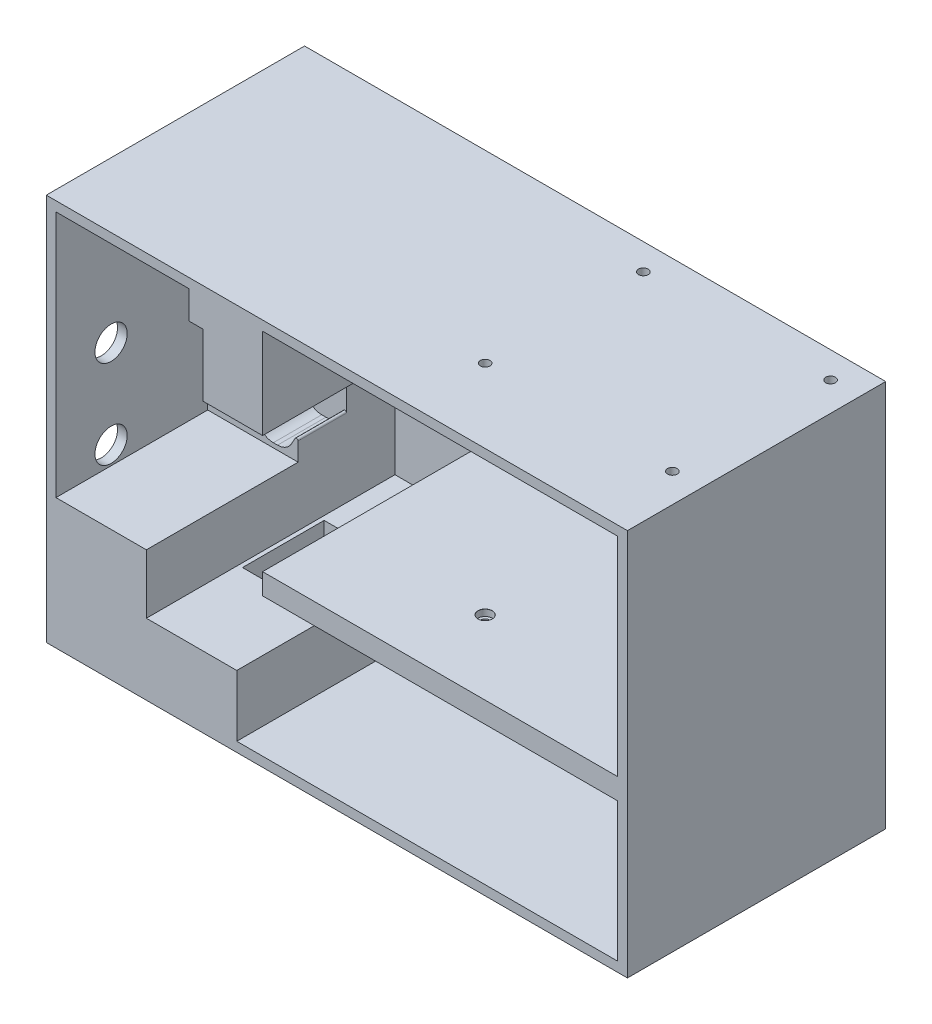
SolidWorks part; units mm, degrees
other "Electronics Cartridge"
ref_plane "Front Plane" through (0, 0, 0) normal (1, 0, 0) x (0, 1, 0)
ref_plane "Top Plane" through (0, 0, 0) normal (0, 0, 1) x (0, 1, 0)
ref_plane "Right Plane" through (0, 0, 0) normal (0, 1, 0) x (-1, 0, 0)
sketch "Sketch1" plane through (0, 0, 0) normal (0, 0, 1) x (0, 1, 0)
  line L1 (60, -90) -> (-60, -90)
  line L2 (60, -90) -> (60, 90)
  line L3 (60, 90) -> (-60, 90)
  line L4 (-60, -90) -> (-60, 90)
  line L5 (60, -90) -> (-60, 90) construction
  line L6 (60, 90) -> (-60, -90) construction
  point P0 (0, 0)
  dimension "D1" = 120
  dimension "D2" = 180
extrude "Boss-Extrude1" add sketch "Sketch1" along normal blind 80
extrude "Cut-Extrude2" cut sketch "Sketch4" against normal blind 77
sketch "Sketch4" plane through (-1315.6499, -737.3472, 80) normal (0, 0, 1) x (1, 0, 0)
  line L4 (1289.6499, 766.3472) -> (1256.6499, 766.3472)
  line L6 (1405.6499, 797.3472) -> (1405.6499, 794.3472)
  line L8 (1405.6499, 794.3472) -> (1402.6499, 794.3472)
  line L9 (1405.6499, 677.3472) -> (1405.6499, 680.3472)
  line L10 (1402.6499, 794.3472) -> (1292.6499, 794.3472)
  line L11 (1402.6499, 794.3472) -> (1402.6499, 729.8472)
  line L12 (1402.6499, 729.8472) -> (1292.6499, 729.8472)
  line L13 (1292.6499, 794.3472) -> (1292.6499, 729.8472)
  line L14 (1405.6499, 680.3472) -> (1402.6499, 680.3472)
  line L15 (1225.6499, 797.3472) -> (1225.6499, 794.3472)
  line L16 (1402.6499, 680.3472) -> (1292.6499, 680.3472)
  line L17 (1402.6499, 680.3472) -> (1402.6499, 723.3472)
  line L18 (1402.6499, 723.3472) -> (1292.6499, 723.3472)
  line L19 (1292.6499, 680.3472) -> (1292.6499, 723.3472)
  line L21 (1225.6499, 794.3472) -> (1228.6499, 794.3472)
  line L22 (1225.6499, 677.3472) -> (1267.6499, 677.3472)
  line L23 (1228.6499, 794.3472) -> (1256.6499, 794.3472)
  line L24 (1228.6499, 794.3472) -> (1228.6499, 730.3472)
  line L25 (1228.6499, 730.3472) -> (1256.6499, 730.3472)
  line L26 (1256.6499, 794.3472) -> (1256.6499, 730.3472)
  line L28 (1267.6499, 677.3472) -> (1267.6499, 680.3472)
  line L29 (1289.6499, 699.3472) -> (1292.6499, 699.3472)
  line L30 (1267.6499, 680.3472) -> (1289.6499, 680.3472)
  line L31 (1267.6499, 680.3472) -> (1267.6499, 699.3472)
  line L32 (1267.6499, 699.3472) -> (1289.6499, 699.3472)
  line L33 (1289.6499, 680.3472) -> (1289.6499, 699.3472)
  line L34 (1292.6499, 723.3472) -> (1292.6499, 729.8472)
  line L35 (1292.6499, 699.3472) -> (1289.6499, 699.3472)
  line L36 (1267.6499, 699.3472) -> (1256.6499, 699.3472)
  line L37 (1256.6499, 699.3472) -> (1256.6499, 729.8472)
  line L38 (1292.6499, 794.3472) -> (1289.6499, 794.3472)
  line L39 (1289.6499, 794.3472) -> (1289.6499, 766.3472)
  line L40 (1289.6499, 766.3472) -> (1292.6499, 766.3472)
  line L41 (1256.6499, 794.3472) -> (1289.6499, 794.3472)
  line L42 (1289.6499, 766.3472) -> (1289.6499, 794.3472)
  line L43 (1256.6499, 699.3472) -> (1292.6499, 699.3472)
  line L44 (1256.6499, 699.3472) -> (1256.6499, 766.3472)
  line L45 (1256.6499, 766.3472) -> (1292.6499, 766.3472)
  line L46 (1292.6499, 699.3472) -> (1292.6499, 766.3472)
  line L47 (1289.6499, 794.3472) -> (1256.6499, 794.3472)
  line L48 (1256.6499, 766.3472) -> (1256.6499, 794.3472)
extrude "Cut-Extrude3" cut sketch "Sketch5" against normal up to surface (77 mm away)
sketch "Sketch5" plane through (-1315.6499, -737.3472, 80) normal (0, 0, 1) x (1, 0, 0)
  line L1 (1256.6499, 794.3472) -> (1274.6499, 794.3472)
  line L2 (1256.6499, 794.3472) -> (1256.6499, 766.3472)
  line L3 (1256.6499, 766.3472) -> (1274.6499, 766.3472)
  line L4 (1274.6499, 794.3472) -> (1274.6499, 766.3472)
sketch "Sketch7" plane through (0, 0, 3) normal (0, 0, 1) x (1, 0, 0)
  line L0 (-59, 48.4969) -> (-66.5056, 48.4969)
  line L1 (-67.9618, 57) -> (-66.5056, 48.4969)
  line L2 (-59, 57) -> (-67.9618, 57)
  line L3 (-59, 57) -> (-59, 48.4969)
  line L4 (-78.0382, -7) -> (-79.4944, 1.5031)
  line L5 (-59, 57) -> (-67.9618, 57)
  line L6 (-59, 57) -> (-59, 48.4969)
  line L7 (-59, 48.4969) -> (-66.5056, 48.4969)
  line L8 (-67.9618, 57) -> (-66.5056, 48.4969)
  line L9 (-74.9296, 57) -> (-71.1195, 57)
  line L13 (-87, 1.5031) -> (-79.4944, 1.5031)
  line L14 (-87, -7) -> (-87, 1.5031)
  line L15 (-87, -7) -> (-78.0382, -7)
  line L16 (-78.0382, -7) -> (-77.996, -7)
  line L17 (-87, 1.5031) -> (-79.4944, 1.5031)
  line L18 (-87, -7) -> (-87, 1.5031)
  line L19 (-87, -7) -> (-78.0382, -7)
  line L20 (-79.4944, 1.5031) -> (-77.996, -7)
  line L21 (-79.4944, 1.5031) -> (-77.996, -7)
  line L22 (-87, 1.5031) -> (-79.4944, 1.5031)
  line L23 (-87, -7) -> (-87, 1.5031)
  line L24 (-77.996, -7) -> (-87, -7)
  line L25 (-79.4944, 1.5031) -> (-77.996, -7)
  line L26 (-74.9296, -7) -> (-77.996, -7)
  line L27 (-87, -7) -> (-59, -7)
  line L28 (-59, 57) -> (-59, -7)
  line L29 (-66.5056, 1.5031) -> (-68.004, -7)
  line L30 (-59, 1.5031) -> (-66.5056, 1.5031)
  line L31 (-59, -7) -> (-59, 1.5031)
  line L32 (-87, 57) -> (-59, 57)
  line L33 (-87, 57) -> (-87, -7)
  line L34 (-79.4944, 1.5031) -> (-77.996, -7)
  line L35 (-87, 1.5031) -> (-79.4944, 1.5031)
  line L36 (-87, 1.5031) -> (-87, -7)
  line L37 (-66.5056, 48.4969) -> (-68.004, 57)
  line L38 (-59, 48.4969) -> (-66.5056, 48.4969)
  line L39 (-59, 48.4969) -> (-59, 57)
  line L40 (-71.0704, 57) -> (-71.1195, 47.7071)
  line L42 (-87, 25) -> (-59, 25)
  line L43 (-73, -7) -> (-73, 47.7071)
  line L44 (-87, 48.4969) -> (-87, 56.702)
  line L45 (-87, 48.4969) -> (-79.4944, 48.4969)
  line L46 (-79.4944, 48.4969) -> (-77.996, 57)
  line L47 (-77.996, 57) -> (-74.9296, 57)
  line L48 (-74.9296, 57) -> (-74.8805, 47.7071)
  line L49 (-74.9296, -7) -> (-71.1153, -7)
  line L52 (-74.9296, -7) -> (-74.9296, 1.5031)
  line L53 (-74.9296, -7) -> (-74.8805, 2.2929)
  line L54 (-74.9296, 57) -> (-77.996, 57)
  line L55 (-79.4944, 48.4969) -> (-77.996, 57)
  line L56 (-77.996, 57) -> (-87, 57)
  line L57 (-87, 57) -> (-87, 48.4969)
  line L58 (-87, 48.4969) -> (-79.4944, 48.4969)
  line L59 (-79.4944, 48.4969) -> (-77.996, 57)
  line L60 (-79.4944, 48.4969) -> (-77.996, 57)
  line L61 (-87, 57) -> (-78.0382, 57)
  line L62 (-87, 57) -> (-87, 48.4969)
  line L63 (-87, 48.4969) -> (-79.4944, 48.4969)
  line L65 (-78.0382, 57) -> (-77.996, 57)
  line L66 (-74.9296, 1.5031) -> (-71.1153, 1.5031)
  line L67 (-87, 57) -> (-78.0382, 57)
  line L68 (-87, 57) -> (-87, 48.4969)
  line L69 (-87, 48.4969) -> (-79.4944, 48.4969)
  line L70 (-78.0382, 57) -> (-79.4944, 48.4969)
  line L71 (-74.9296, -7) -> (-74.8805, 2.2929)
  line L72 (-77.996, -7) -> (-74.9296, -7)
  line L73 (-79.4944, 1.5031) -> (-77.996, -7)
  line L74 (-87, 1.5031) -> (-79.4944, 1.5031)
  line L75 (-87, 1.5031) -> (-87, -6.702)
  line L77 (-71.0704, -7) -> (-71.1195, 2.2929)
  line L78 (-59, 1.5031) -> (-59, -7)
  line L79 (-59, 1.5031) -> (-66.5056, 1.5031)
  line L80 (-66.5056, 1.5031) -> (-68.004, -7)
  line L81 (-87, -7) -> (-59, -7)
  line L82 (-67.9618, -7) -> (-66.5056, 1.5031)
  line L83 (-59, 1.5031) -> (-66.5056, 1.5031)
  line L84 (-59, -7) -> (-59, 1.5031)
  line L85 (-59, -7) -> (-67.9618, -7)
  line L86 (-59, -7) -> (-59, 1.5031)
  line L87 (-59, -7) -> (-67.9618, -7)
  line L88 (-67.9618, -7) -> (-66.5056, 1.5031)
  line L89 (-59, 1.5031) -> (-66.5056, 1.5031)
  line L90 (-71.1153, -7) -> (-71.1153, 1.5031)
  line L91 (-71.1195, -7) -> (-71.1195, 2.2929)
  line L92 (-74.9296, -7) -> (-71.1195, -7)
  line L93 (-74.9296, -7) -> (-74.9296, 2.2929)
  line L94 (-74.9296, 57) -> (-71.1153, 57)
  line L95 (-87, -7) -> (-77.996, -7)
  line L96 (-87, -7) -> (-87, 1.5031)
  line L97 (-87, 1.5031) -> (-79.4944, 1.5031)
  line L98 (-77.996, -7) -> (-79.4944, 1.5031)
  line L99 (-74.9296, -7) -> (-71.1195, -7)
  line L100 (-74.9296, -7) -> (-74.9296, 2.2929)
  line L102 (-71.1195, -7) -> (-71.1195, 2.2929)
  line L103 (-59, -7) -> (-67.9618, -7)
  line L104 (-59, -7) -> (-59, 1.5031)
  line L105 (-59, 1.5031) -> (-66.5056, 1.5031)
  line L106 (-67.9618, -7) -> (-66.5056, 1.5031)
  line L107 (-74.9296, 57) -> (-74.9296, 48.4969)
  line L108 (-74.9296, 48.4969) -> (-71.1153, 48.4969)
  line L109 (-71.1153, 57) -> (-71.1153, 48.4969)
extrude "Boss-Extrude2" add sketch "Sketch7" along normal blind 15
sketch "Sketch8" plane through (0, 0, 80) normal (0, 0, 1) x (1, 0, 0)
  line L0 (-59, -38) -> (-59, -7) construction
  line L1 (-87, -7) -> (-59, -7)
  line L2 (-87, -7) -> (-87, -19.6386)
  line L3 (-87, -19.6386) -> (-59, -19.6386)
  line L4 (-59, -7) -> (-59, -19.6386)
extrude "Cut-Extrude4" cut sketch "Sketch8" against normal up to surface (62 mm away) up to face at (-63.1168, -2.7485, 18)
sketch "Sketch10" plane through (-41, 0, 0) normal (-1, 0, 0) x (0, -1, 0)
  line L1 (-57, 3) -> (-29, 3)
  line L2 (-57, 3) -> (-57, 80)
  line L3 (-57, 80) -> (-29, 80)
  line L4 (-29, 3) -> (-29, 80)
extrude "Boss-Extrude5" add sketch "Sketch10" along normal blind 4.8
sketch "Sketch12" plane through (0, 0, 18) normal (0, 0, 1) x (1, 0, 0)
  line L0 (-59, -11.9813) -> (-62.4048, -18.2506)
  line L1 (-59, -19.6386) -> (-59, 1.5031) construction
  line L2 (-62.4048, -18.2506) -> (-69.5659, -18.2506)
  line L3 (-69.5659, -18.2506) -> (-74.4091, -9.8383)
  line L4 (-74.4091, -9.8383) -> (-87, -9.8383)
  line L5 (-87, -19.6386) -> (-87, 1.5031) construction
  line L6 (-87, -9.8383) -> (-87, -19.6386)
  line L7 (-87, -19.6386) -> (-59, -19.6386)
  line L8 (-59, -19.6386) -> (-59, -11.9813)
extrude "Boss-Extrude6" add sketch "Sketch12" along normal blind 15
fillet "Fillet1" radius 0.5 1 edges at (-59, -11.9813, 25.5)
fillet "Fillet2" radius 5 2 edges at (-69.5659, -18.2506, 25.5) (-62.4048, -18.2506, 25.5)
sketch "Sketch13" plane through (0, -14, 0) normal (0, -1, 0) x (1, 0, 0)
  circle A0 centre (23.054, 57.1239) radius 1.35
  circle A1 centre (23.054, 8.1239) radius 1.35
  circle A2 centre (81.054, 8.1239) radius 1.3523
  circle A3 centre (81.054, 57.1239) radius 1.3599
hole_wizard "CBORE for M2 SHCS1" positions "Sketch14" profile "Sketch15" counterbore size "M2" standard "ANSI Metric"
sketch "Sketch14" plane through (0, -7.5, 0) normal (0, 1, 0) x (-1, 0, 0)
  point P0 (-81.054, 57.1239)
  point P3 (-23.054, 57.1239)
  point P6 (-81.054, 8.1239)
  point P9 (-23.054, 8.1239)
sketch "Sketch15" plane through (81.054, -7.5, 57.1239) normal (1, 0, 0) x (0, 0, 1)
  line L0 (0, 0) -> (0, 7.2811)
  line L1 (0, 7.2811) -> (1.3, 6.5)
  line L2 (1.3, 6.5) -> (1.3, 2)
  line L3 (1.3, 2) -> (2.2, 2)
  line L5 (2.2, 2) -> (2.2, 0.025)
  line L6 (2.2, 0.025) -> (2.225, 0)
  line L7 (2.225, 0) -> (0, 0)
  line L8 (-2.2, 0.025) -> (-2.225, 0) construction
  line L10 (0, 7.2811) -> (-1.3, 6.5) construction
  line L11 (0, -6.35) -> (0, 107.95) construction
  dimension "Hole Dia." = 2.6
  dimension "Hole Depth" = 6.5
  dimension "C'Bore Dia." = 4.4
  dimension "C'Bore Depth" = 2
  dimension "Near C'Sink Dia." = 4.45
  dimension "Near C'Sink Angle" = 90
  dimension "Drill Angle" = 118
sketch "Sketch16" plane through (0, -60, 0) normal (0, -1, 0) x (1, 0, 0)
  line L0 (-90, 80) -> (90, 80) construction
  line L1 (-90, 0) -> (-58.3106, 0)
  line L2 (-90, 0) -> (-90, 80)
  line L3 (-90, 80) -> (-58.3106, 80)
  line L4 (-58.3106, 0) -> (-58.3106, 80)
ref_plane "Plane1" through (0, 0, 60) normal (0, 0, 1) x (0, -1, 0)
sketch "Sketch18" plane through (0, 0, 60) normal (0, 0, 1) x (0, -1, 0)
  line L0 (62.758, -84.3002) -> (62.758, -70.4353)
  line L1 (62.758, -70.4353) -> (58.0568, -70.4353)
  line L2 (58.0568, -70.4353) -> (55.7265, -68.1051)
  line L3 (55.7265, -68.1051) -> (52.1556, -68.1051)
  line L4 (52.1556, -68.1051) -> (52.1556, -78.5426)
  line L5 (52.1556, -78.5426) -> (55.7265, -84.3002)
  line L6 (55.7265, -84.3002) -> (62.758, -84.3002)
extrude "Cut-Extrude8" cut sketch "Sketch18" against normal blind 45 and the other way blind 3
fillet "Fillet3" radius 2 5 edges at (-84.3002, -55.7265, 39) (-70.4353, -58.0568, 39) (-84.3002, -60, 39) (-78.5426, -52.1556, 39) (-68.1051, -52.1556, 39)
sketch "Sketch21" plane through (-90, 0, 0) normal (-1, 0, 0) x (0, -1, 0)
  line L1 (-60, 80) -> (60, 80) construction
  circle A0 centre (14, 62.9369) radius 5
  circle A1 centre (-13.3683, 62.9369) radius 5
  dimension "D1" = 10
  dimension "D2" = 10
  dimension "D3" = 17.0631
extrude "Cut-Extrude9" cut sketch "Sketch21" against normal blind 25
sketch "Sketch22" plane through (0, -57, 0) normal (0, 1, 0) x (-1, 0, 0)
  line L0 (26, 3) -> (26, 80) construction
  line L1 (26, 3) -> (48, 3)
  line L2 (26, 3) -> (26, 80)
  line L3 (26, 80) -> (48, 80)
  line L4 (48, 3) -> (48, 80)
  line L5 (48, 3) -> (26, 3) construction
extrude "Boss-Extrude7" add sketch "Sketch22" along normal blind 19
sketch "Sketch23" plane through (0, -60, 0) normal (0, -1, 0) x (1, 0, 0)
  line L1 (-43.3938, 48.8071) -> (-56.3938, 48.8071)
  line L2 (-43.3938, 48.8071) -> (-43.3938, 29.3071)
  line L3 (-43.3938, 29.3071) -> (-56.3938, 29.3071)
  line L4 (-56.3938, 48.8071) -> (-56.3938, 29.3071)
  line L5 (-43.3938, 48.8071) -> (-56.3938, 29.3071) construction
  line L6 (-43.3938, 29.3071) -> (-56.3938, 48.8071) construction
  point P0 (-49.8938, 39.0571)
  dimension "D1" = 19.5
  dimension "D2" = 13
extrude "Cut-Extrude10" cut sketch "Sketch23" against normal blind 30
sketch "Sketch24" plane through (0, -60, 0) normal (0, -1, 0) x (1, 0, 0)
  line L0 (-43.3938, 39.0571) -> (-56.3938, 39.0571)
  line L1 (-43.3938, 29.3071) -> (-56.3938, 29.3071)
  line L2 (-43.3938, 29.3071) -> (-43.3938, 48.8071)
  line L3 (-43.3938, 48.8071) -> (-56.3938, 48.8071)
  line L4 (-56.3938, 29.3071) -> (-56.3938, 48.8071)
  line L5 (-41.8938, 50.0571) -> (-57.8938, 50.0571)
  line L6 (-41.8938, 50.0571) -> (-41.8938, 28.0571)
  line L7 (-41.8938, 28.0571) -> (-57.8938, 28.0571)
  line L8 (-57.8938, 50.0571) -> (-57.8938, 28.0571)
  line L9 (-41.8938, 50.0571) -> (-57.8938, 28.0571) construction
  line L10 (-41.8938, 28.0571) -> (-57.8938, 50.0571) construction
  line L11 (-49.8938, 48.8071) -> (-49.8938, 29.3071)
  point P6 (-49.8938, 39.0571)
  dimension "D1" = 22
  dimension "D2" = 16
extrude "Cut-Extrude11" cut sketch "Sketch24" against normal blind 8 contours L6 L5 L8 L7
sketch "Sketch25" plane through (0, -38, 0) normal (0, 1, 0) x (-1, 0, 0)
  line L1 (45.5203, 48.9123) -> (43.3938, 48.9123)
  line L2 (45.5203, 48.9123) -> (45.5203, 29.3071)
  line L3 (45.5203, 29.3071) -> (43.3938, 29.3071)
  line L4 (43.3938, 48.9123) -> (43.3938, 29.3071)
  line L5 (42.4498, 26.2169) -> (57.7152, 26.2169)
  line L6 (42.4498, 26.2169) -> (42.4498, 51.5132)
  line L7 (42.4498, 51.5132) -> (57.7152, 51.5132)
  line L8 (57.7152, 26.2169) -> (57.7152, 51.5132)
  line L9 (42.4498, 26.2169) -> (57.7152, 51.5132) construction
  line L10 (42.4498, 51.5132) -> (57.7152, 26.2169) construction
  point P5 (50.0825, 38.8651)
extrude "Cut-Extrude12" cut sketch "Sketch25" against normal blind 12 contours L6 L5 L8 L7
sketch "Sketch26" plane through (0, -7.5, 0) normal (0, 1, 0) x (-1, 0, 0)
  circle A0 centre (-23.054, 57.1239) radius 1.5
  circle A1 centre (-23.054, 8.1239) radius 1.5
  circle A2 centre (-81.054, 8.1239) radius 1.5
  circle A3 centre (-81.054, 57.1239) radius 1.5
  dimension "D1" = 3
  dimension "D2" = 3
  dimension "D3" = 3
  dimension "D4" = 3
extrude "Cut-Extrude13" cut sketch "Sketch26" along normal blind 73
sketch "Sketch27" plane through (0, 1.5031, 0) normal (0, 1, 0) x (-1, 0, 0)
  line L1 (74.9296, 3) -> (71.1153, 3)
  line L2 (74.9296, 3) -> (74.9296, 18)
  line L3 (74.9296, 18) -> (71.1153, 18)
  line L4 (71.1153, 3) -> (71.1153, 18)
extrude "Cut-Extrude14" cut sketch "Sketch27" against normal blind 2 and the other way blind 49
sketch "Sketch28" plane through (0, 0, 80) normal (0, 0, 1) x (1, 0, 0)
  line L1 (-87, -19.6386) -> (-41.4203, -19.6386)
  line L2 (-87, -19.6386) -> (-87, 48.3193)
  line L3 (-87, 48.3193) -> (-41.4203, 48.3193)
  line L4 (-41.4203, -19.6386) -> (-41.4203, 48.3193)
extrude "Cut-Extrude15" cut sketch "Sketch28" against normal blind 29
sketch "Sketch29" plane through (-23, 0, 0) normal (1, 0, 0) x (0, 1, 0)
  line L1 (-57, 3) -> (-38, 3)
  line L2 (-57, 3) -> (-57, 80)
  line L3 (-57, 80) -> (-38, 80)
  line L4 (-38, 3) -> (-38, 80)
extrude "Cut-Extrude17" cut sketch "Sketch29" against normal blind 8
sketch "Sketch30" plane through (0, -14, 0) normal (0, -1, 0) x (1, 0, 0)
  line L1 (87, 3) -> (-4.154, 3)
  line L2 (87, 3) -> (87, 63.6226)
  line L3 (87, 63.6226) -> (-4.154, 63.6226)
  line L4 (-4.154, 3) -> (-4.154, 63.6226)
  circle A0 centre (23.054, 8.1239) radius 3
  circle A1 centre (23.054, 57.1239) radius 3
  circle A2 centre (81.054, 8.1239) radius 3
  circle A3 centre (81.054, 57.1239) radius 3
  dimension "D1" = 6
  dimension "D2" = 6
  dimension "D3" = 6
  dimension "D4" = 6
extrude "Cut-Extrude18" cut sketch "Sketch30" against normal blind 3
fillet "Fillet4" radius 5 3 edges at (-4.154, -12.5, 3) (-4.154, -12.5, 63.6226) (87, -12.5, 63.6226)
